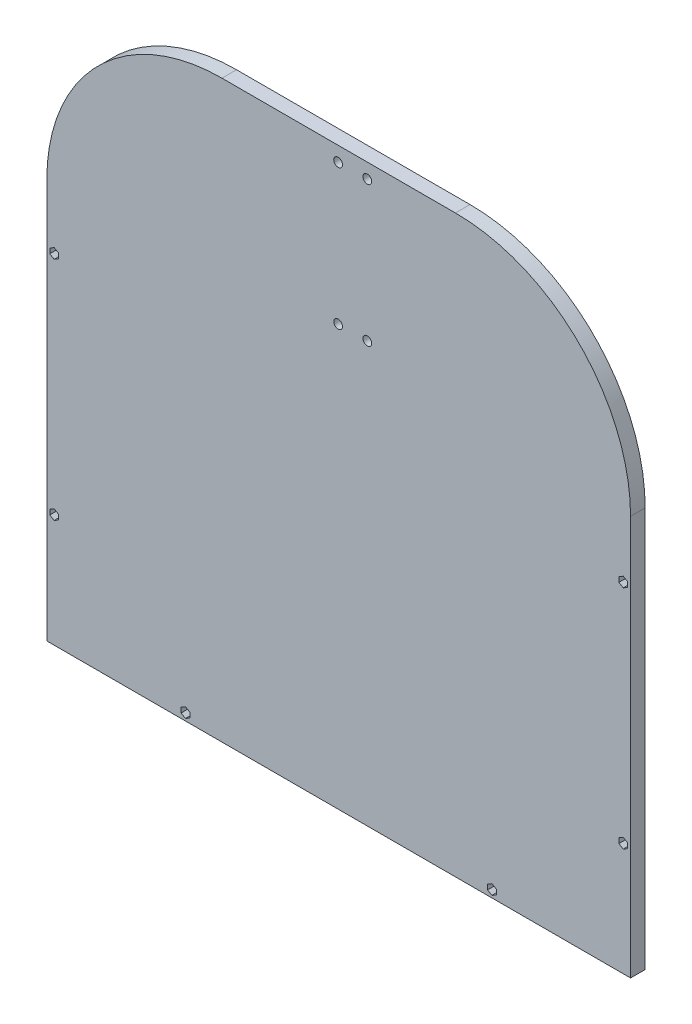
SolidWorks part; units mm, degrees
ref_plane "Plan de face" through (0, 0, 0) normal (0, 0, 1) x (1, 0, 0)
ref_plane "Plan de dessus" through (0, 0, 0) normal (0, 1, 0) x (1, 0, 0)
ref_plane "Plan de droite" through (0, 0, 0) normal (1, 0, 0) x (0, 0, -1)
sketch "Esquisse1" plane through (0, 0, 0) normal (0, 0, 1) x (1, 0, 0)
  line L1 (-100, 77.5) -> (100, 77.5)
  line L2 (-100, 77.5) -> (-100, -77.5)
  line L3 (-100, -77.5) -> (100, -77.5)
  line L4 (100, 77.5) -> (100, -77.5)
  line L5 (-100, 77.5) -> (100, -77.5) construction
  line L6 (-100, -77.5) -> (100, 77.5) construction
  point P0 (0, 0)
  dimension "D1" = 155
  dimension "D2" = 200
extrude "Boss.-Extru.1" add sketch "Esquisse1" along normal blind 5
sketch "Esquisse2" plane through (0, 0, 5) normal (0, 0, 1) x (1, 0, 0)
  line L0 (100, 77.5) -> (-100, 77.5) construction
  line L1 (-96, 37.884) -> (-96, 39.616)
  line L2 (-96, 39.616) -> (-97.5, 40.4821)
  line L3 (-97.5, 40.4821) -> (-99, 39.616)
  line L4 (-99, 39.616) -> (-99, 37.884)
  line L5 (-99, 37.884) -> (-97.5, 37.0179)
  line L6 (-97.5, 37.0179) -> (-96, 37.884)
  line L7 (-100, 77.5) -> (-100, -77.5) construction
  line L8 (-112.59, 0) -> (147.7632, 0) construction
  line L9 (-97.5, -37.0179) -> (-96, -37.884)
  line L10 (-99, -37.884) -> (-97.5, -37.0179)
  line L11 (-99, -39.616) -> (-99, -37.884)
  line L12 (-97.5, -40.4821) -> (-99, -39.616)
  line L13 (-96, -39.616) -> (-97.5, -40.4821)
  line L14 (-96, -37.884) -> (-96, -39.616)
  line L15 (0, 108.077) -> (0, -98.6079) construction
  line L16 (99, -37.884) -> (97.5, -37.0179)
  line L17 (99, -39.616) -> (99, -37.884)
  line L18 (97.5, -40.4821) -> (99, -39.616)
  line L19 (96, -39.616) -> (97.5, -40.4821)
  line L20 (96, -37.884) -> (96, -39.616)
  line L21 (97.5, -37.0179) -> (96, -37.884)
  line L22 (97.5, 37.0179) -> (96, 37.884)
  line L23 (99, 37.884) -> (97.5, 37.0179)
  line L24 (99, 39.616) -> (99, 37.884)
  line L25 (97.5, 40.4821) -> (99, 39.616)
  line L26 (96, 39.616) -> (97.5, 40.4821)
  line L27 (96, 37.884) -> (96, 39.616)
  line L28 (-100, -77.5) -> (100, -77.5) construction
  line L29 (-51, -75.866) -> (-51, -74.134)
  line L30 (-51, -74.134) -> (-52.5, -73.2679)
  line L31 (-52.5, -73.2679) -> (-54, -74.134)
  line L32 (-54, -74.134) -> (-54, -75.866)
  line L33 (-54, -75.866) -> (-52.5, -76.7321)
  line L34 (-52.5, -76.7321) -> (-51, -75.866)
  line L35 (52.5, -76.7321) -> (51, -75.866)
  line L36 (54, -75.866) -> (52.5, -76.7321)
  line L37 (54, -74.134) -> (54, -75.866)
  line L38 (52.5, -73.2679) -> (54, -74.134)
  line L39 (51, -74.134) -> (52.5, -73.2679)
  line L40 (51, -75.866) -> (51, -74.134)
  circle A0 centre (-97.5, 38.75) radius 1.5 construction
  circle A1 centre (-52.5, -75) radius 1.5 construction
  dimension "D2" = 3
  dimension "D5" = 3
  dimension "D1" = 2.5
  dimension "155/4" = 38.75
  dimension "D3" = 2.5
  dimension "D4" = 47.5
extrude "Enlèv. mat.-Extru.1" cut sketch "Esquisse2" against normal through all
sketch "Esquisse4" plane through (0, 77.5, 0) normal (0, 1, 0) x (1, 0, 0)
  line L4 (100, 0) -> (-100, 0)
  line L5 (-100, 0) -> (-100, -5)
  line L6 (-100, -5) -> (100, -5)
  line L7 (100, -5) -> (100, 0)
  line L8 (100, 0) -> (-100, 0)
  line L9 (-100, 0) -> (-100, -5)
  line L10 (-100, -5) -> (100, -5)
  line L11 (100, -5) -> (100, 0)
  dimension "D1" = 0
extrude "Boss.-Extru.2" add sketch "Esquisse4" along normal blind 42
fillet "Congé1" radius 60 2 edges at (100, 119.5, 2.5) (-100, 119.5, 2.5)
sketch "Esquisse5" plane through (0, 0, 0) normal (0, 0, -1) x (-1, 0, 0)
  circle A0 centre (-9.8, 66.4472) radius 1.5
  circle A1 centre (0.2, 66.4472) radius 1.5
  circle A2 centre (-9.8, 114.4472) radius 1.5
  circle A3 centre (0.2, 114.4472) radius 1.5
extrude "Enlèv. mat.-Extru.2" cut sketch "Esquisse5" against normal blind 17
